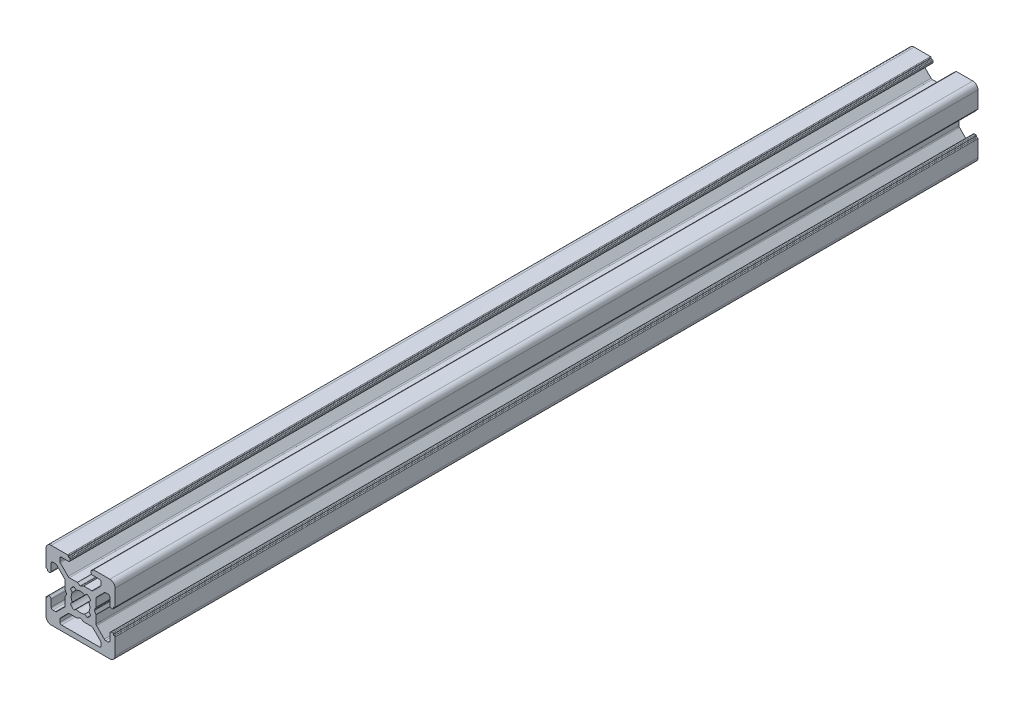
SolidWorks part; units mm, degrees
ref_plane "Front Plane" through (0, 0, 0) normal (0, 0, 1) x (1, 0, 0)
ref_plane "Top Plane" through (0, 0, 0) normal (0, 1, 0) x (1, 0, 0)
ref_plane "Right Plane" through (0, 0, 0) normal (1, 0, 0) x (0, 0, -1)
sketch "Sketch1" plane through (0, 0, 0) normal (0, 0, 1) x (1, 0, 0)
  line L0 (-5.5, -8.5) -> (5.5, -8.5)
  line L1 (3, 9) -> (3, 9.3)
  line L2 (4.6464, 3.5858) -> (6.9142, 5.8536)
  line L3 (3.5858, 4.6464) -> (5.8536, 6.9142)
  line L4 (6, 7.2678) -> (6, 8)
  line L5 (3.55, 9.7) -> (3.55, 9.8)
  line L6 (3.2, 9.5) -> (3.35, 9.5)
  line L7 (3.5, 8.5) -> (5.5, 8.5)
  line L8 (3.75, 10) -> (8.5, 10)
  line L9 (10, 3.75) -> (10, 8.5)
  line L10 (8.5, 3.45) -> (8.5, 5.5)
  line L11 (9, 2.95) -> (9.3, 2.95)
  line L12 (7.2678, 6) -> (8, 6)
  line L13 (9.5, 3.15) -> (9.5, 3.35)
  line L14 (9.7, 3.55) -> (9.8, 3.55)
  line L15 (9, -3.05) -> (9.3, -3.05)
  line L16 (3.5858, -4.6464) -> (5.8536, -6.9142)
  line L17 (4.6464, -3.5858) -> (6.9142, -5.8536)
  line L18 (7.2678, -6) -> (8, -6)
  line L19 (9.7, -3.55) -> (9.8, -3.55)
  line L20 (9.5, -3.25) -> (9.5, -3.35)
  line L21 (8.5, -3.55) -> (8.5, -5.5)
  line L22 (10, -3.75) -> (10, -8.5)
  line L23 (-8.5, -10) -> (8.5, -10)
  line L24 (6, -7.2678) -> (6, -8)
  line L25 (-0.8536, 4.4732) -> (-0.1, 4.0381)
  line L26 (-3.2322, 4.5) -> (-0.9536, 4.5)
  line L27 (-1.2353, 2.4008) -> (-1.8871, 2.9477)
  line L28 (-0.8536, -4.4732) -> (-0.1, -4.0381)
  line L29 (-3.2322, -4.5) -> (-0.9536, -4.5)
  line L30 (-2.4008, 1.2353) -> (-2.9477, 1.8871)
  line L31 (-4.5, -3.2322) -> (-4.5, -0.9536)
  line L32 (-4.4732, -0.8536) -> (-4.0381, -0.1)
  line L33 (-4.4732, 0.8536) -> (-4.0381, 0.1)
  line L34 (-4.5, 3.2322) -> (-4.5, 0.9536)
  line L35 (-1.2353, -2.4008) -> (-1.8871, -2.9477)
  line L36 (-2.4008, -1.2353) -> (-2.9477, -1.8871)
  line L37 (-6, -7.2678) -> (-6, -8)
  line L38 (-10, -3.75) -> (-10, -8.5)
  line L39 (-8.5, -3.55) -> (-8.5, -5.5)
  line L40 (-9.5, -3.25) -> (-9.5, -3.35)
  line L41 (2.4008, -1.2353) -> (2.9477, -1.8871)
  line L42 (1.2353, -2.4008) -> (1.8871, -2.9477)
  line L43 (-9.7, -3.55) -> (-9.8, -3.55)
  line L44 (-7.2678, -6) -> (-8, -6)
  line L45 (-4.6464, -3.5858) -> (-6.9142, -5.8536)
  line L46 (-3.5858, -4.6464) -> (-5.8536, -6.9142)
  line L47 (4.5, 3.2322) -> (4.5, 0.9536)
  line L48 (4.4732, 0.8536) -> (4.0381, 0.1)
  line L49 (4.4732, -0.8536) -> (4.0381, -0.1)
  line L50 (4.5, -3.2322) -> (4.5, -0.9536)
  line L51 (2.4008, 1.2353) -> (2.9477, 1.8871)
  line L52 (3.2322, -4.5) -> (0.9536, -4.5)
  line L53 (0.8536, -4.4732) -> (0.1, -4.0381)
  line L54 (-9, -3.05) -> (-9.3, -3.05)
  line L55 (-9.7, 3.55) -> (-9.8, 3.55)
  line L56 (-9.5, 3.15) -> (-9.5, 3.35)
  line L57 (-7.2678, 6) -> (-8, 6)
  line L58 (-9, 2.95) -> (-9.3, 2.95)
  line L59 (-8.5, 3.45) -> (-8.5, 5.5)
  line L60 (-10, 3.75) -> (-10, 8.5)
  line L61 (-3.75, 10) -> (-8.5, 10)
  line L62 (1.2353, 2.4008) -> (1.8871, 2.9477)
  line L63 (-3.5, 8.5) -> (-5.5, 8.5)
  line L64 (-3.2, 9.5) -> (-3.35, 9.5)
  line L65 (3.2322, 4.5) -> (0.9536, 4.5)
  line L66 (0.8536, 4.4732) -> (0.1, 4.0381)
  line L67 (-3.55, 9.7) -> (-3.55, 9.8)
  line L68 (-6, 7.2678) -> (-6, 8)
  line L69 (-3.5858, 4.6464) -> (-5.8536, 6.9142)
  line L70 (-4.6464, 3.5858) -> (-6.9142, 5.8536)
  line L71 (-3, 9) -> (-3, 9.3)
  line L72 (0, 12.5156) -> (0, -13.063) construction
  line L73 (-12.1519, 0) -> (11.4074, 0) construction
  arc A0 (-0.9536, 4.5) -> (-0.8536, 4.4732) centre (-0.9536, 4.3) cw
  arc A1 (-3.2322, 4.5) -> (-3.5858, 4.6464) centre (-3.2322, 5) cw
  arc A2 (9, -3.05) -> (8.5, -3.55) centre (9, -3.55) ccw
  arc A3 (8.5, 3.45) -> (9, 2.95) centre (9, 3.45) ccw
  arc A4 (3, 9) -> (3.5, 8.5) centre (3.5, 9) ccw
  arc A5 (-3.5858, -4.6464) -> (-3.2322, -4.5) centre (-3.2322, -5) cw
  arc A6 (6, 8) -> (5.5, 8.5) centre (5.5, 8) ccw
  arc A7 (5.8536, 6.9142) -> (6, 7.2678) centre (5.5, 7.2678) ccw
  arc A8 (3.35, 9.5) -> (3.55, 9.7) centre (3.35, 9.7) ccw
  arc A9 (3.75, 10) -> (3.55, 9.8) centre (3.75, 9.8) ccw
  arc A10 (3.2, 9.5) -> (3, 9.3) centre (3.2, 9.3) ccw
  arc A11 (8.5, 5.5) -> (8, 6) centre (8, 5.5) ccw
  arc A12 (10, 8.5) -> (8.5, 10) centre (8.5, 8.5) ccw
  arc A13 (7.2678, 6) -> (6.9142, 5.8536) centre (7.2678, 5.5) ccw
  arc A14 (9.3, 2.95) -> (9.5, 3.15) centre (9.3, 3.15) ccw
  arc A15 (9.8, 3.55) -> (10, 3.75) centre (9.8, 3.75) ccw
  arc A16 (9.7, 3.55) -> (9.5, 3.35) centre (9.7, 3.35) ccw
  arc A17 (8, -6) -> (8.5, -5.5) centre (8, -5.5) ccw
  arc A18 (6.9142, -5.8536) -> (7.2678, -6) centre (7.2678, -5.5) ccw
  arc A19 (9.5, -3.35) -> (9.7, -3.55) centre (9.7, -3.35) ccw
  arc A20 (10, -3.75) -> (9.8, -3.55) centre (9.8, -3.75) ccw
  arc A21 (9.5, -3.25) -> (9.3, -3.05) centre (9.3, -3.25) ccw
  arc A22 (5.5, -8.5) -> (6, -8) centre (5.5, -8) ccw
  arc A23 (8.5, -10) -> (10, -8.5) centre (8.5, -8.5) ccw
  arc A24 (6, -7.2678) -> (5.8536, -6.9142) centre (5.5, -7.2678) ccw
  arc A25 (-0.8536, -4.4732) -> (-0.9536, -4.5) centre (-0.9536, -4.3) cw
  arc A26 (-4.6464, 3.5858) -> (-4.5, 3.2322) centre (-5, 3.2322) cw
  arc A27 (-4.5, -3.2322) -> (-4.6464, -3.5858) centre (-5, -3.2322) cw
  arc A28 (-4.4732, 0.8536) -> (-4.5, 0.9536) centre (-4.3, 0.9536) cw
  arc A29 (-4.5, -0.9536) -> (-4.4732, -0.8536) centre (-4.3, -0.9536) cw
  arc A30 (-4.0381, 0.1) -> (-4.0381, -0.1) centre (-4.2113, 0) cw
  arc A31 (-2.9477, 1.8871) -> (-1.8871, 2.9477) centre (0, 0) cw
  arc A32 (-1.8871, -2.9477) -> (-2.9477, -1.8871) centre (0, 0) cw
  arc A33 (-2.4008, -1.2353) -> (-2.4008, 1.2353) centre (0, 0) cw
  arc A34 (-6, -7.2678) -> (-5.8536, -6.9142) centre (-5.5, -7.2678) cw
  arc A35 (-8.5, -10) -> (-10, -8.5) centre (-8.5, -8.5) cw
  arc A36 (-5.5, -8.5) -> (-6, -8) centre (-5.5, -8) cw
  arc A37 (-9.5, -3.25) -> (-9.3, -3.05) centre (-9.3, -3.25) cw
  arc A38 (-10, -3.75) -> (-9.8, -3.55) centre (-9.8, -3.75) cw
  arc A39 (2.4008, -1.2353) -> (2.4008, 1.2353) centre (0, 0) ccw
  arc A40 (-1.2353, -2.4008) -> (1.2353, -2.4008) centre (0, 0) ccw
  arc A41 (-9.5, -3.35) -> (-9.7, -3.55) centre (-9.7, -3.35) cw
  arc A42 (1.8871, -2.9477) -> (2.9477, -1.8871) centre (0, 0) ccw
  arc A43 (-6.9142, -5.8536) -> (-7.2678, -6) centre (-7.2678, -5.5) cw
  arc A44 (-8, -6) -> (-8.5, -5.5) centre (-8, -5.5) cw
  arc A45 (2.9477, 1.8871) -> (1.8871, 2.9477) centre (0, 0) ccw
  arc A46 (4.0381, 0.1) -> (4.0381, -0.1) centre (4.2113, 0) ccw
  arc A47 (4.5, -0.9536) -> (4.4732, -0.8536) centre (4.3, -0.9536) ccw
  arc A48 (4.4732, 0.8536) -> (4.5, 0.9536) centre (4.3, 0.9536) ccw
  arc A49 (4.5, -3.2322) -> (4.6464, -3.5858) centre (5, -3.2322) ccw
  arc A50 (4.6464, 3.5858) -> (4.5, 3.2322) centre (5, 3.2322) ccw
  arc A51 (0.1, -4.0381) -> (-0.1, -4.0381) centre (0, -4.2113) ccw
  arc A52 (-9.7, 3.55) -> (-9.5, 3.35) centre (-9.7, 3.35) cw
  arc A53 (0.8536, -4.4732) -> (0.9536, -4.5) centre (0.9536, -4.3) ccw
  arc A54 (-9.8, 3.55) -> (-10, 3.75) centre (-9.8, 3.75) cw
  arc A55 (3.5858, -4.6464) -> (3.2322, -4.5) centre (3.2322, -5) ccw
  arc A56 (-9.3, 2.95) -> (-9.5, 3.15) centre (-9.3, 3.15) cw
  arc A57 (-7.2678, 6) -> (-6.9142, 5.8536) centre (-7.2678, 5.5) cw
  arc A58 (-10, 8.5) -> (-8.5, 10) centre (-8.5, 8.5) cw
  arc A59 (-8.5, 5.5) -> (-8, 6) centre (-8, 5.5) cw
  arc A60 (-3.2, 9.5) -> (-3, 9.3) centre (-3.2, 9.3) cw
  arc A61 (-3.75, 10) -> (-3.55, 9.8) centre (-3.75, 9.8) cw
  arc A62 (-3.35, 9.5) -> (-3.55, 9.7) centre (-3.35, 9.7) cw
  arc A63 (-5.8536, 6.9142) -> (-6, 7.2678) centre (-5.5, 7.2678) cw
  arc A64 (3.2322, 4.5) -> (3.5858, 4.6464) centre (3.2322, 5) ccw
  arc A65 (-6, 8) -> (-5.5, 8.5) centre (-5.5, 8) cw
  arc A66 (-3, 9) -> (-3.5, 8.5) centre (-3.5, 9) cw
  arc A67 (-8.5, 3.45) -> (-9, 2.95) centre (-9, 3.45) cw
  arc A68 (-9, -3.05) -> (-8.5, -3.55) centre (-9, -3.55) cw
  arc A69 (0.9536, 4.5) -> (0.8536, 4.4732) centre (0.9536, 4.3) ccw
  arc A70 (-0.1, 4.0381) -> (0.1, 4.0381) centre (0, 4.2113) ccw
  arc A71 (1.2353, 2.4008) -> (-1.2353, 2.4008) centre (0, 0) ccw
  point P214 (0, -10)
  point P215 (0, -8.5)
  dimension "D1" = 20
  dimension "D2" = 20
  dimension "D3" = 6
  dimension "D4" = 6
  dimension "D5" = 10
  dimension "D6" = 5.5
  dimension "D7" = 6
extrude "Extrude1" add sketch "Sketch1" along normal blind 250
